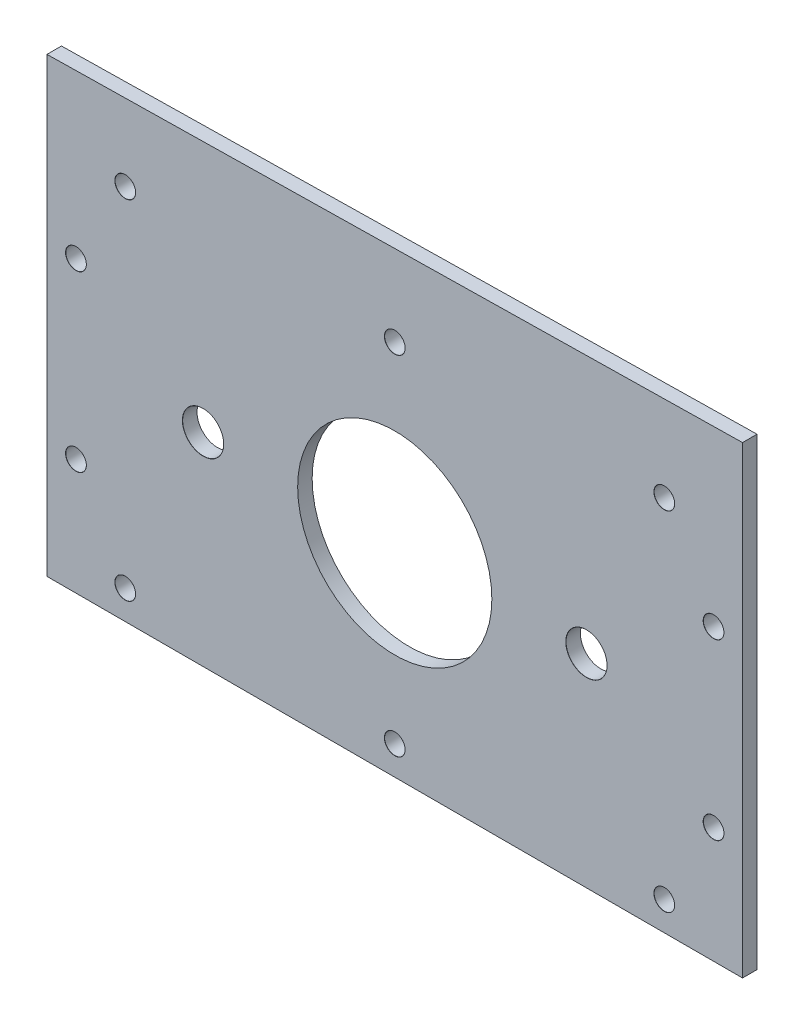
SolidWorks part; units mm, degrees
material "Alloy Steel (SS)"
ref_plane "X-Y Datum" through (0, 0, 0) normal (0, 0, 1) x (1, 0, 0)
ref_plane "X-Z Datum" through (0, 0, 0) normal (0, 1, 0) x (1, 0, 0)
ref_plane "Y-Z Datum" through (0, 0, 0) normal (1, 0, 0) x (0, 0, -1)
sketch "Sketch1" plane through (0, 0, 0) normal (0, 0, 1) x (1, 0, 0)
  line L0 (-76.2, 54.61) -> (-76.2, 44.45)
  line L1 (-76.2, 44.45) -> (76.2, 44.45) construction
  line L2 (-76.2, 44.45) -> (-76.2, -44.45)
  line L3 (-76.2, -44.45) -> (76.2, -44.45)
  line L4 (76.2, 44.45) -> (76.2, -44.45)
  line L5 (-76.2, 44.45) -> (76.2, -44.45) construction
  line L6 (-76.2, -44.45) -> (76.2, 44.45) construction
  line L7 (76.2, 44.45) -> (76.2, 57.15)
  line L10 (-76.2, 54.61) -> (76.2, 57.15)
  point P0 (0, 0)
  dimension "D1" = 152.4
  dimension "D2" = 88.9
  dimension "D3" = 12.7
  dimension "D4" = 10.16
extrude "Boss-Extrude1" add sketch "Sketch1" along normal blind 3.175
hole_wizard "M4 Clearance Hole1" positions "Sketch7" profile "Sketch8" hole size "M4" standard "ANSI Metric" end condition through all
sketch "Sketch7" plane through (0, 0, 3.175) normal (0, 0, 1) x (1, 0, 0)
  line L0 (-75.8701, 0) -> (49924.1299, 0) construction
  line L1 (0, 56.7764) -> (0, -49943.2236) construction
  line L2 (-76.2, -44.45) -> (76.2, -44.45) construction
  line L10 (-76.2, 0) -> (76.2, 0) construction
  line L11 (-76.2, 54.61) -> (-76.2, -44.45) construction
  line L12 (76.2, -44.45) -> (76.2, 57.15) construction
  line L14 (-69.85, -44.45) -> (-69.85, 54.7158) construction
  line L15 (-76.2, -44.45) -> (76.2, -44.45) construction
  line L16 (76.2, 57.15) -> (-76.2, 54.61) construction
  line L17 (69.85, -44.45) -> (69.85, 57.0442) construction
  line L18 (59.055, -44.45) -> (59.055, 56.8642) construction
  line L20 (-59.055, -44.45) -> (-59.055, 54.8957) construction
  line L21 (-76.2, -38.1) -> (76.2, -38.1) construction
  line L22 (-76.2, 19.05) -> (76.2, 19.05) construction
  line L23 (-76.2, -19.05) -> (76.2, -19.05) construction
  line L24 (-76.2, 38.1) -> (76.2, 38.1) construction
  circle A0 centre (-59.055, 38.1) radius 6.35
  circle A1 centre (0, 38.1) radius 6.35
  circle A2 centre (59.055, 38.1) radius 6.35
  circle A3 centre (69.85, 19.05) radius 6.35
  circle A4 centre (69.85, -19.05) radius 6.35
  circle A5 centre (59.055, -38.1) radius 6.35
  circle A6 centre (0, -38.1) radius 6.35
  circle A7 centre (-59.055, -38.1) radius 6.35
  circle A8 centre (-69.85, -19.05) radius 6.35
  circle A9 centre (-69.85, 19.05) radius 6.35
  point P149 (-59.055, 38.1)
  point P153 (0, 38.1)
  point P155 (59.055, 38.1)
  point P157 (69.85, 19.05)
  point P162 (69.85, -19.05)
  point P164 (59.055, -38.1)
  point P166 (0, -38.1)
  point P168 (-59.055, -38.1)
  point P170 (-69.85, -19.05)
  point P172 (-69.85, 19.05)
  dimension "D1" = 6.35
  dimension "D9" = 12.7
  dimension "D2" = 146.05
  dimension "D3" = 135.255
  dimension "D4" = 6.35
  dimension "D5" = 17.145
  dimension "D6" = 25.4
  dimension "D7" = 63.5
  dimension "D8" = 82.55
sketch "Sketch8" plane through (-69.85, 19.05, 3.175) normal (1, 0, 0) x (0, -1, 0)
  line L0 (0, 0) -> (0, 3.175)
  line L1 (0, 3.175) -> (2.25, 3.175)
  line L2 (2.25, 3.175) -> (2.25, 0.025)
  line L3 (2.25, 0.025) -> (2.275, 0)
  line L5 (2.275, 0) -> (0, 0)
  line L6 (-2.25, 0.025) -> (-2.275, 0) construction
  line L11 (0, -6.35) -> (0, 107.95) construction
  dimension "Thru Hole Dia." = 4.5
  dimension "Thru Hole Depth" = 3.175
  dimension "Near C'Sink Dia." = 4.55
  dimension "Near C'Sink Angle" = 90
sketch "Sketch9" plane through (0, 0, 3.175) normal (0, 0, 1) x (1, 0, 0)
  line L0 (-42, 0) -> (42, 0) construction
  line L1 (0, -44.45) -> (0, 42.6782) construction
  line L2 (-76.2, -44.45) -> (76.2, -44.45) construction
  circle A0 centre (0, 0) radius 21.275
  circle A1 centre (42, 0) radius 4 construction
  circle A2 centre (-42, 0) radius 4 construction
  dimension "D1" = 42.55
  dimension "D3" = 8
  dimension "D2" = 42
hole_wizard "M8 Clearance Hole1" positions "Sketch10" profile "Sketch11" hole size "M8" standard "ANSI Metric" end condition through all
sketch "Sketch10" plane through (0, 0, 3.175) normal (0, 0, 1) x (1, 0, 0)
  point P0 (-42, 0)
  point P3 (42, 0)
sketch "Sketch11" plane through (-42, 0, 3.175) normal (1, 0, 0) x (0, -1, 0)
  line L0 (0, 0) -> (0, 3.175)
  line L1 (0, 3.175) -> (4.5, 3.175)
  line L2 (4.5, 3.175) -> (4.5, 0.025)
  line L3 (4.5, 0.025) -> (4.525, 0)
  line L5 (4.525, 0) -> (0, 0)
  line L6 (-4.5, 0.025) -> (-4.525, 0) construction
  line L11 (0, -6.35) -> (0, 107.95) construction
  dimension "Thru Hole Dia." = 9
  dimension "Thru Hole Depth" = 3.175
  dimension "Near C'Sink Dia." = 9.05
  dimension "Near C'Sink Angle" = 90
extrude "Center Hole" cut sketch "Sketch9" against normal through all
